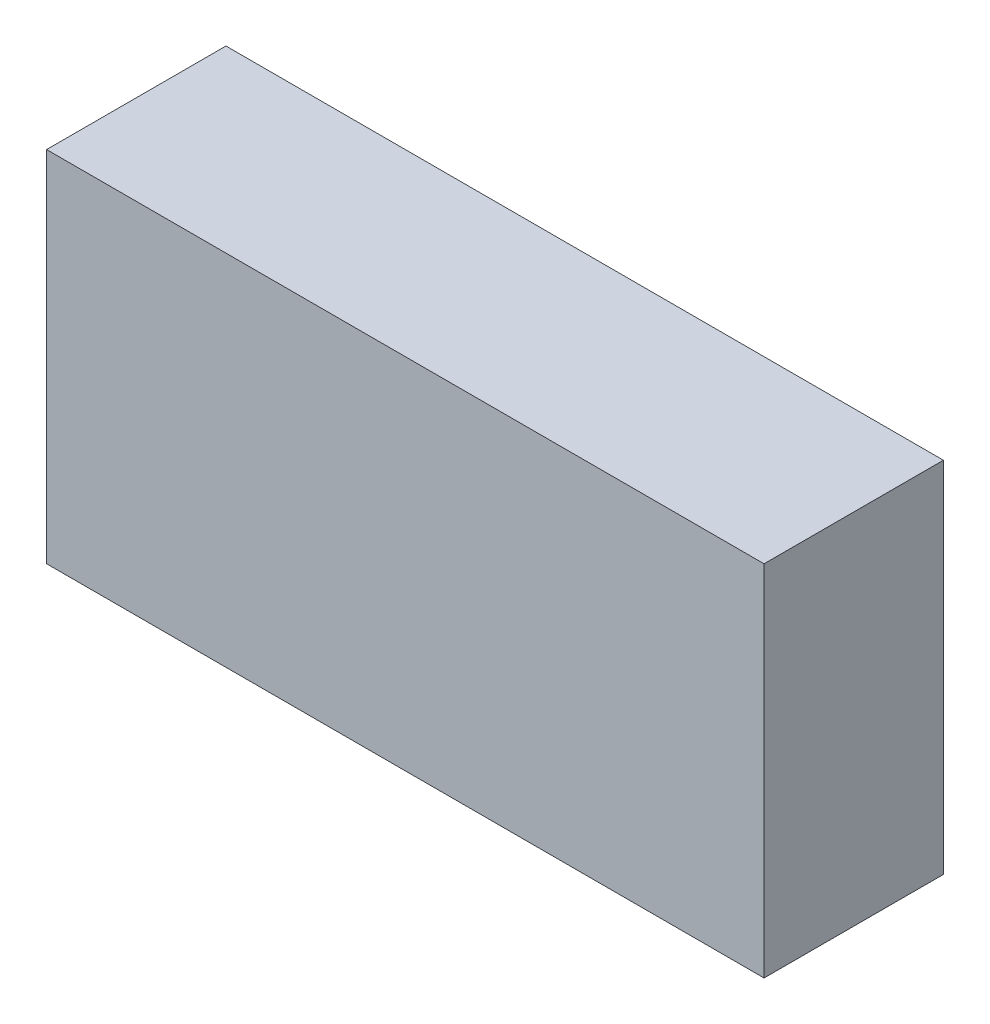
SolidWorks part; units mm, degrees
ref_plane "前视基准面" through (0, 0, 0) normal (0, 0, 1) x (1, 0, 0)
ref_plane "上视基准面" through (0, 0, 0) normal (0, 1, 0) x (1, 0, 0)
ref_plane "右视基准面" through (0, 0, 0) normal (1, 0, 0) x (0, 0, -1)
sketch "草图1" plane through (0, 0, 0) normal (0, 1, 0) x (1, 0, 0)
  line L1 (50, -12.5) -> (-50, -12.5)
  line L2 (50, -12.5) -> (50, 12.5)
  line L3 (50, 12.5) -> (-50, 12.5)
  line L4 (-50, -12.5) -> (-50, 12.5)
  line L5 (50, -12.5) -> (-50, 12.5) construction
  line L6 (50, 12.5) -> (-50, -12.5) construction
  point P0 (0, 0)
  dimension "D1" = 25
  dimension "D2" = 100
extrude "凸台-拉伸1" add sketch "草图1" along normal blind 50
